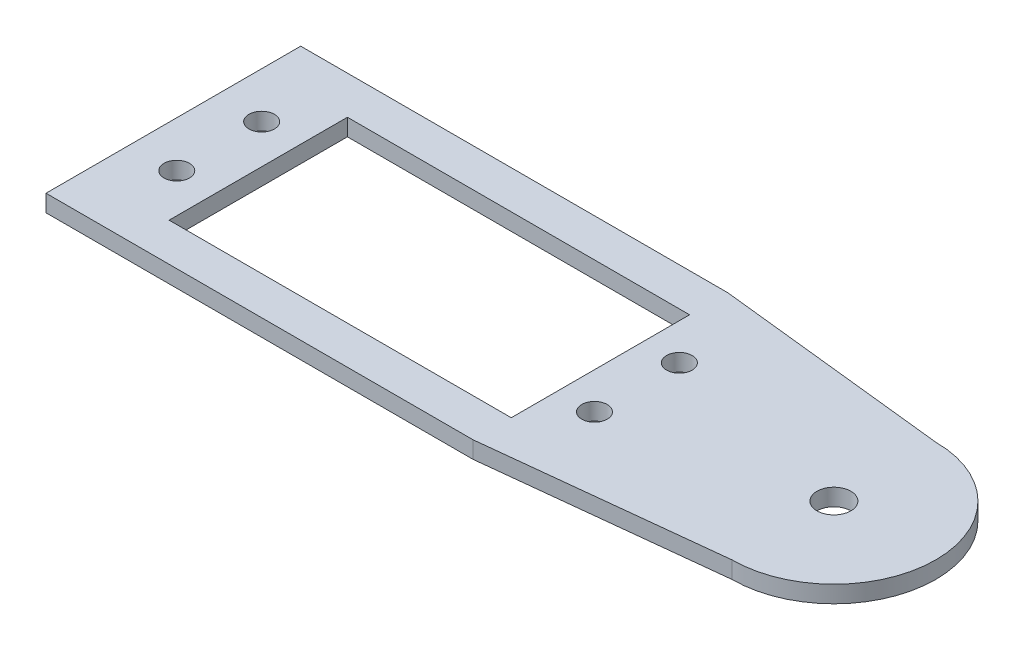
SolidWorks part; units mm, degrees
ref_plane "Спереди" through (0, 0, 0) normal (0, 0, 1) x (1, 0, 0)
ref_plane "Сверху" through (0, 0, 0) normal (0, 1, 0) x (1, 0, 0)
ref_plane "Справа" through (0, 0, 0) normal (1, 0, 0) x (0, 0, -1)
sketch "Эскиз1" plane through (0, 0, 0) normal (0, 1, 0) x (1, 0, 0)
  line L0 (5.4, -5) -> (5.4, 5) construction
  line L5 (10, 10.5) -> (50.3, 10.5)
  line L6 (10, 10.5) -> (10, -10.5) construction
  line L7 (10, -10.5) -> (50.3, -10.5)
  line L8 (5.4, -5) -> (54.6, -5) construction
  line L9 (54.6, -5) -> (54.6, 5) construction
  line L11 (5.4, 5) -> (54.6, 5) construction
  line L18 (50.3, 10.5) -> (50.3, -10.5)
  line L21 (10, -10.5) -> (10, 10.5)
  line L24 (0, 15) -> (50.3, 15)
  line L25 (50.3, 15) -> (77.8, 12)
  line L26 (0, 15) -> (0, -15)
  line L27 (0, -15) -> (50.3, -15)
  line L28 (50.3, -15) -> (77.8, -12)
  line L29 (0, 0) -> (89.8, 0) construction
  circle A0 centre (5.4, -5) radius 1.5
  circle A1 centre (5.4, 5) radius 1.5
  circle A2 centre (54.6, -5) radius 1.5
  circle A3 centre (54.6, 5) radius 1.5
  circle A4 centre (77.8, 0) radius 2
  arc A6 (77.8, -12) -> (77.8, 12) centre (77.8, 0) ccw
  point P0 (50.3, 20.289)
  point P1 (5.4, 0)
  point P2 (10, 0)
  dimension "D6" = 3
  dimension "D9" = 10
  dimension "D10" = 49.2
  dimension "D13" = 4
  dimension "D15" = 12
  dimension "D2" = 30
  dimension "D3" = 40.3
  dimension "D4" = 21
  dimension "D5" = 4.6
  dimension "D7" = 10
  dimension "D16" = 77.8
  dimension "D18" = 50.3
extrude "Основа" add sketch "Эскиз1" along normal blind 2
